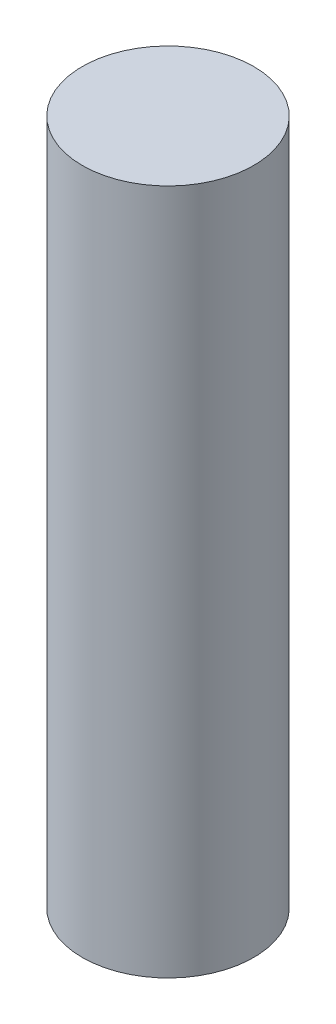
SolidWorks part; units mm, degrees
ref_plane "Piano frontale" through (0, 0, 0) normal (0, 0, 1) x (1, 0, 0)
ref_plane "Piano superiore" through (0, 0, 0) normal (0, 1, 0) x (1, 0, 0)
ref_plane "Piano destro" through (0, 0, 0) normal (1, 0, 0) x (0, 0, -1)
sketch "Schizzo1" plane through (0, 0, 0) normal (0, 1, 0) x (1, 0, 0)
  circle A0 centre (0, 0) radius 6.25
  dimension "D1" = 12.5
extrude "Estrusione-Estrusione1" add sketch "Schizzo1" along normal blind 50
